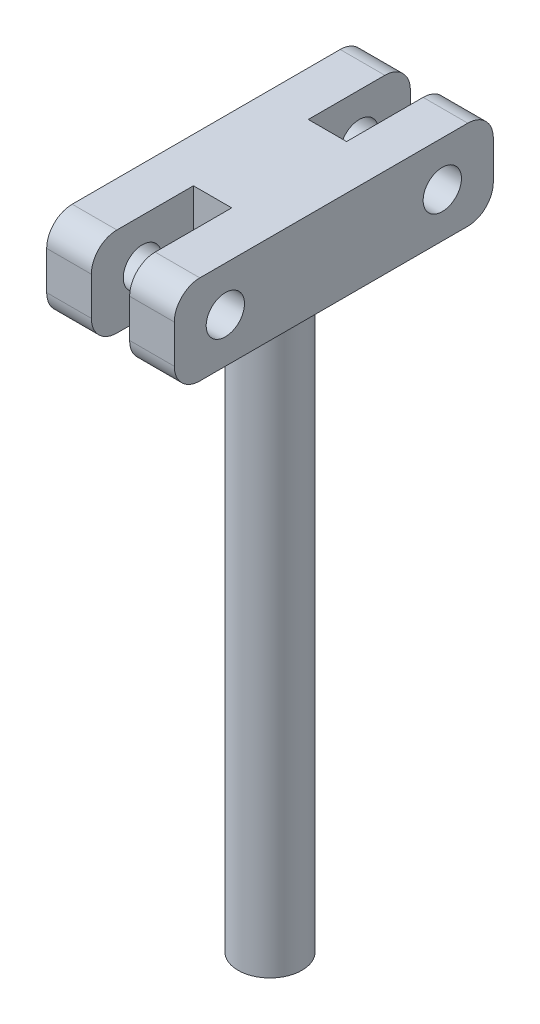
SolidWorks part; units mm, degrees
ref_plane "Alzado" through (0, 0, 0) normal (0, 0, 1) x (1, 0, 0)
ref_plane "Planta" through (0, 0, 0) normal (0, 1, 0) x (1, 0, 0)
ref_plane "Vista lateral" through (0, 0, 0) normal (1, 0, 0) x (0, 0, -1)
sketch "Croquis1" plane through (0, 0, 0) normal (0, 1, 0) x (1, 0, 0)
  circle A0 centre (0, 0) radius 2.5
  dimension "D1" = 5
extrude "Saliente-Extruir1" add sketch "Croquis1" against normal blind 50
sketch "Croquis2" plane through (0, 0, 0) normal (1, 0, 0) x (0, 0, -1)
  line L1 (10.5, -3.5) -> (-10.5, -3.5)
  line L2 (12.5, -1.5) -> (12.5, 1.5)
  line L3 (10.5, 3.5) -> (-10.5, 3.5)
  line L4 (-12.5, -1.5) -> (-12.5, 1.5)
  line L5 (12.5, -3.5) -> (-12.5, 3.5) construction
  line L6 (12.5, 3.5) -> (-12.5, -3.5) construction
  arc A0 (-12.5, 1.5) -> (-10.5, 3.5) centre (-10.5, 1.5) cw
  arc A1 (-12.5, -1.5) -> (-10.5, -3.5) centre (-10.5, -1.5) ccw
  arc A2 (10.5, 3.5) -> (12.5, 1.5) centre (10.5, 1.5) cw
  arc A3 (12.5, -1.5) -> (10.5, -3.5) centre (10.5, -1.5) cw
  circle A4 centre (-8.5, 0) radius 1.5
  circle A5 centre (8.5, 0) radius 1.5
  point P0 (0, 0)
  dimension "D3" = 2
  dimension "D4" = 2
  dimension "D5" = 2
  dimension "D6" = 2
  dimension "D9" = 3
  dimension "D10" = 3
  dimension "D1" = 25
  dimension "D2" = 7
  dimension "D7" = 4
  dimension "D8" = 4
extrude "Saliente-Extruir2" add sketch "Croquis2" along normal mid plane 10
sketch "Croquis3" plane through (0, 3.5, 0) normal (0, 1, 0) x (1, 0, 0)
  line L0 (5, 12.5) -> (-5, 12.5) construction
  line L1 (-1.5, 4.5) -> (1.5, 4.5)
  line L2 (-1.5, 4.5) -> (-1.5, 12.5)
  line L3 (-1.5, 12.5) -> (1.5, 12.5)
  line L4 (1.5, 4.5) -> (1.5, 12.5)
  line L5 (-1.5, 4.5) -> (1.5, 12.5) construction
  line L6 (-1.5, 12.5) -> (1.5, 4.5) construction
  line L7 (5, -12.5) -> (-5, -12.5) construction
  line L8 (-1.5, -4.5) -> (1.5, -4.5)
  line L9 (-1.5, -4.5) -> (-1.5, -12.5)
  line L10 (-1.5, -12.5) -> (1.5, -12.5)
  line L11 (1.5, -4.5) -> (1.5, -12.5)
  line L12 (-1.5, -4.5) -> (1.5, -12.5) construction
  line L13 (-1.5, -12.5) -> (1.5, -4.5) construction
  point P0 (0, 8.5)
  point P7 (0, -8.5)
  dimension "D1" = 3
  dimension "D2" = 3
  dimension "D3" = 8
  dimension "D4" = 8
extrude "Cortar-Extruir1" cut sketch "Croquis3" against normal through all both and the other way through all
